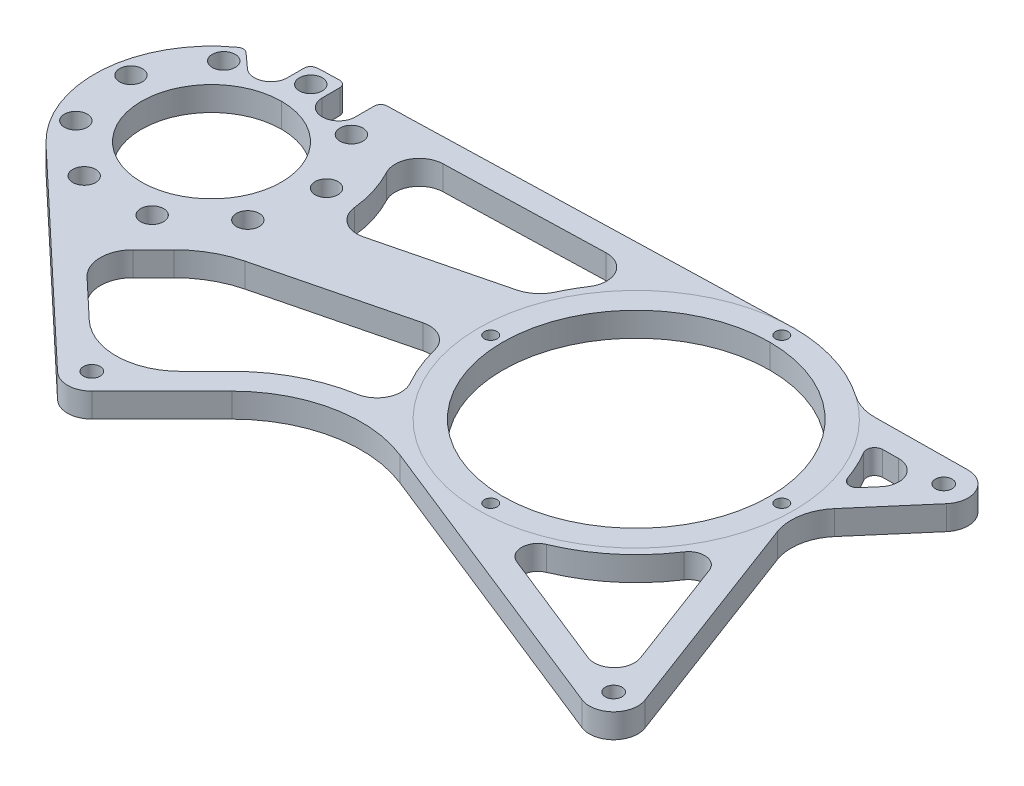
SolidWorks part; units mm, degrees
material "6061-T6 (SS)"
ref_plane "X-Y Datum" through (0, 0, 0) normal (0, 0, 1) x (1, 0, 0)
ref_plane "X-Z Datum" through (0, 0, 0) normal (0, 1, 0) x (1, 0, 0)
ref_plane "Y-Z Datum" through (0, 0, 0) normal (1, 0, 0) x (0, 0, -1)
sketch "Master Sketch " plane through (0, 0, 0) normal (0, 1, 0) x (1, 0, 0)
  line L0 (0, 0) -> (116.84, 0) construction
  line L1 (0, 0) -> (-54.61, 0) construction
  line L2 (116.84, 0) -> (228.6, 0) construction
  line L3 (228.6, 0) -> (228.6, 165.1) construction
  line L4 (123.19, 0) -> (123.19, 116.0018) construction
  line L5 (-54.61, 0) -> (-414.02, 0) construction
  line L6 (-54.61, 0) -> (-54.61, 127) construction
  line L7 (123.19, 168.4528) -> (123.19, 177.9778) construction
  line L8 (123.19, 116.0018) -> (228.6, 165.1) construction
  line L9 (123.19, 116.0018) -> (228.6, 0) construction
  line L10 (0, 0) -> (123.19, 116.0018) construction
  line L11 (0, 0) -> (-54.61, 127) construction
  line L12 (-54.61, 127) -> (123.19, 116.0018) construction
  line L13 (-54.61, 127) -> (228.6, 165.1) construction
  line L14 (0, 0) -> (0, 123.622) construction
  line L15 (-86.1521, 93.553) -> (-6.535, 18.4704)
  line L16 (-54.61, 172.974) -> (123.19, 177.9778)
  line L17 (192.5164, 124.5578) -> (212.8001, 148.1685)
  line L18 (169.599, 163.5141) -> (205.4727, 163.8999)
  line L19 (189.1339, 105.4429) -> (220.4344, 22.1488)
  line L20 (6.7352, 18.6648) -> (34.256, 46.1856)
  line L21 (207.987, 9.9519) -> (89.0101, 57.4446)
  circle A0 centre (0, 0) radius 12.7 construction
  circle A1 centre (228.6, 165.1) radius 12.7 construction
  circle A2 centre (228.6, 0) radius 12.7 construction
  circle A3 centre (-414.02, 0) radius 12.7 construction
  circle A4 centre (123.19, 116.0018) radius 52.451
  circle A5 centre (123.19, 116.0018) radius 57.15 construction
  circle A6 centre (123.19, 116.0018) radius 61.976 construction
  circle A7 centre (-54.61, 127) radius 45.974
  circle A8 centre (-54.61, 127) radius 39 construction
  circle A9 centre (205.5752, 154.3754) radius 3 construction
  circle A10 centre (211.5182, 18.7982) radius 3 construction
  circle A11 centre (0, 25.4) radius 3 construction
  circle A12 centre (0, 25.4) radius 9.525
  circle A13 centre (211.5182, 18.7982) radius 9.525
  circle A14 centre (205.5752, 154.3754) radius 9.525
  arc A17 (56.2619, 120.1418) -> (168.2859, 66.3745) centre (123.19, 116.0018) ccw construction
  arc A18 (123.19, 177.9778) -> (158.5311, 166.9138) centre (123.19, 116.0018) cw
  circle A19 centre (123.19, 116.0018) radius 67.056 construction
  arc A20 (192.5164, 124.5578) -> (189.1339, 105.4429) centre (206.9663, 112.1441) ccw
  arc A21 (169.599, 163.5141) -> (158.5311, 166.9138) centre (169.3942, 182.563) cw
  arc A22 (89.0101, 57.4446) -> (34.256, 46.1856) centre (70.177, 10.2646) ccw
  circle A23 centre (-54.61, 127) radius 25.908 construction
  circle A24 centre (-54.61, 127) radius 27.4955
  circle A25 centre (123.19, 173.1518) radius 2.5 construction
  circle A26 centre (-41.2712, 163.648) radius 6.5
  circle A27 centre (-67.9488, 163.648) radius 6.5
  point P9 (123.19, 0)
  point P23 (-54.61, 166)
  point P27 (-41.2712, 163.648)
  point P28 (-29.5413, 156.8757)
  point P29 (-20.835, 146.5)
  point P30 (-16.2025, 133.7723)
  point P31 (-16.2025, 120.2277)
  point P32 (-20.835, 107.5)
  point P33 (-29.5413, 97.1243)
  point P34 (-41.2712, 90.352)
  point P35 (-54.61, 88)
  point P36 (-67.9488, 90.352)
  point P37 (-79.6787, 97.1243)
  point P38 (-88.385, 107.5)
  point P39 (-93.0175, 120.2277)
  point P40 (-93.0175, 133.7723)
  point P41 (-88.385, 146.5)
  point P42 (-79.6787, 156.8757)
  point P43 (-67.9488, 163.648)
  point P44 (-54.61, 127)
  point P66 (190.246, 116.0018)
  point P74 (185.166, 116.0018)
  point P77 (163.0683, 163.4438)
  point P80 (74.3713, 70.0317)
  dimension "D1" = 105.41
  dimension "D2" = 25.4
  dimension "D8" = 116.0018
  dimension "D11" = 104.902
  dimension "D12" = 114.3
  dimension "D13" = 123.952
  dimension "D14" = 91.948
  dimension "D15" = 78
  dimension "D17" = 6
  dimension "D21" = 19.05
  dimension "D23" = 13
  dimension "D25" = 19.05
  dimension "D26" = 19.05
  dimension "D27" = 50.8
  dimension "D28" = 1.5875
  dimension "D30" = 51.816
  dimension "D31" = 5
  dimension "D3" = 165.1
  dimension "D4" = 171.45
  dimension "D5" = 111.76
  dimension "D6" = 116.84
  dimension "D7" = 54.61
  dimension "D9" = 642.62
  dimension "D10" = 127
  dimension "D18" = 25.4
  dimension "D19" = 25.4
  dimension "D20" = 25.4
  dimension "D22" = 228.6
  dimension "D29" = 45
  dimension "D24" = 5.08
  dimension "D16" = 18
extrude "Boss-Extrude2" add sketch "Master Sketch " along normal mid plane 9.525
hole_wizard "Ø5.0mm Dowel Hole1" positions "Sketch26" profile "Sketch27" hole size "Ø5.0" standard "ANSI Metric" end condition through all
sketch "Sketch26" plane through (0, 4.7625, 0) normal (0, 1, 0) x (1, 0, 0)
  point P5 (123.19, 173.1518)
sketch "Sketch27" plane through (123.19, 4.7625, -173.1518) normal (1, 0, 0) x (0, 0, 1)
  line L0 (0, 0) -> (0, 9.525)
  line L1 (0, 9.525) -> (2.5, 9.525)
  line L2 (2.5, 9.525) -> (2.5, 0)
  line L5 (2.5, 0) -> (0, 0)
  line L11 (0, -6.35) -> (0, 107.95) construction
  dimension "Thru Hole Dia." = 5
  dimension "Thru Hole Depth" = 9.525
pattern_circular "CirPattern4" count 4 over 360 about axis through (123.19, 0, -116.0018) along (0, 1, 0) of "Ø5.0mm Dowel Hole1"
hole_wizard "M6 Clearance Hole4" positions "Sketch20" profile "Sketch21" hole size "M6" standard "ANSI Metric" end condition through all
sketch "Sketch20" plane through (0, 4.7625, 0) normal (0, 1, 0) x (1, 0, 0)
  point P0 (205.5752, 154.3754)
  point P3 (211.5182, 18.7982)
  point P6 (0, 25.4)
  point P9 (205.5752, 154.3754)
sketch "Sketch21" plane through (205.5752, 4.7625, -154.3754) normal (1, 0, 0) x (0, 0, 1)
  line L0 (0, 0) -> (0, 9.525)
  line L1 (0, 9.525) -> (3.3, 9.525)
  line L2 (3.3, 9.525) -> (3.3, 0)
  line L5 (3.3, 0) -> (0, 0)
  line L11 (0, -6.35) -> (0, 107.95) construction
  dimension "Thru Hole Dia." = 6.6
  dimension "Thru Hole Depth" = 9.525
hole_wizard "M8 Clearance Hole1" positions "Sketch24" profile "Sketch25" hole size "M8" standard "ANSI Metric" end condition through all
sketch "Sketch24" plane through (0, 4.7625, 0) normal (0, 1, 0) x (1, 0, 0)
  point P2 (-54.61, 166)
sketch "Sketch25" plane through (-54.61, 4.7625, -166) normal (1, 0, 0) x (0, 0, 1)
  line L0 (0, 0) -> (0, 9.525)
  line L1 (0, 9.525) -> (4.5, 9.525)
  line L2 (4.5, 9.525) -> (4.5, 0)
  line L5 (4.5, 0) -> (0, 0)
  line L11 (0, -6.35) -> (0, 107.95) construction
  dimension "Thru Hole Dia." = 9
  dimension "Thru Hole Depth" = 9.525
pattern_circular "CirPattern3" count 9 over 360 about axis through (-54.61, 0, -127) along (0, 1, 0) of "M8 Clearance Hole1"
ref_plane "Plane2" through (-54.61, 0, 0) normal (1, 0, 0) x (0, 0, -1)
ref_plane "Plane1" through (123.19, 0, 0) normal (1, 0, 0) x (0, 0, -1)
split line "Split Line2"
split line "Split Line3"
ref_point "Point2"
ref_point "Point3"
sketch "Sketch28" plane through (0, 4.7625, 0) normal (0, 1, 0) x (1, 0, 0)
  circle A0 centre (123.19, 116.0018) radius 61.976 construction
  circle A1 centre (123.19, 116.0018) radius 61.976
split line "Split Line4"
sketch "Topology 3" plane through (0, 4.7625, 0) normal (0, 1, 0) x (1, 0, 0)
  line L0 (148.2326, 44.0603) -> (194.8213, 25.4632)
  line L1 (205.1941, 35.6272) -> (188.9001, 78.9873)
  line L2 (188.0448, 154.1869) -> (181.8702, 154.1205)
  line L3 (190.1271, 136.3935) -> (194.151, 141.0774)
  line L4 (185.2915, 130.7647) -> (205.5752, 154.3754) construction
  line L5 (17.4418, 42.8418) -> (27.5208, 52.9208)
  line L6 (-33.0328, 56.5514) -> (-17.9453, 42.3233)
  line L7 (119.7044, 177.8797) -> (-54.61, 172.974)
  line L8 (-86.1521, 93.553) -> (-6.535, 18.4704)
  line L9 (6.7352, 18.6648) -> (34.256, 46.1856)
  line L10 (89.0101, 57.4446) -> (207.987, 9.9519)
  line L11 (220.4344, 22.1488) -> (189.1339, 105.4429)
  line L12 (192.5164, 124.5578) -> (212.8001, 148.1685)
  line L13 (205.4727, 163.8999) -> (169.599, 163.5141)
  line L14 (119.7044, 177.8797) -> (-54.61, 172.974)
  line L15 (-86.1521, 93.553) -> (-6.535, 18.4704)
  line L16 (6.7352, 18.6648) -> (34.256, 46.1856)
  line L17 (89.0101, 57.4446) -> (207.987, 9.9519)
  line L18 (220.4344, 22.1488) -> (189.1339, 105.4429)
  line L19 (192.5164, 124.5578) -> (212.8001, 148.1685)
  line L20 (205.4727, 163.8999) -> (169.599, 163.5141)
  line L22 (-7.4578, 92.9346) -> (48.4864, 106.9206)
  line L23 (60.6168, 166.688) -> (-1.6638, 164.9353)
  line L24 (7.6514, 124.4645) -> (55.6594, 136.4665)
  line L25 (-33.2997, 74.7712) -> (-25.158, 82.9129)
  line L26 (119.9724, 168.3585) -> (-54.342, 163.4528) construction
  line L27 (-79.6171, 100.4826) -> (0, 25.4) construction
  line L28 (0, 25.4) -> (27.5208, 52.9208) construction
  line L29 (92.5413, 66.2908) -> (211.5182, 18.7982) construction
  line L30 (211.5182, 18.7982) -> (180.2176, 102.0923) construction
  line L32 (205.5752, 154.3754) -> (169.7015, 153.9896) construction
  arc A0 (123.19, 54.0258) -> (182.1581, 96.9285) centre (123.19, 116.0018) ccw
  arc A1 (148.1536, 55.8231) -> (177.6482, 80.2392) centre (123.19, 116.0018) ccw
  arc A2 (172.1385, 154.0158) -> (183.7852, 129.0114) centre (123.19, 116.0018) cw
  arc A3 (179.1759, 149.3219) -> (184.7202, 137.4188) centre (123.19, 116.0018) cw
  arc A4 (59.8962, 69.7071) -> (27.5208, 52.9208) centre (70.177, 10.2646) ccw
  arc A7 (61.4889, 110.1712) -> (82.4046, 69.3373) centre (123.19, 116.0018) ccw
  arc A8 (158.5311, 166.9138) -> (169.599, 163.5141) centre (169.3942, 182.563) ccw
  arc A9 (119.7044, 177.8797) -> (158.5311, 166.9138) centre (123.19, 116.0018) ccw
  arc A10 (-54.61, 172.974) -> (-86.1521, 93.553) centre (-54.61, 127) ccw
  arc A11 (-6.535, 18.4704) -> (6.7352, 18.6648) centre (0, 25.4) ccw
  arc A12 (89.0101, 57.4446) -> (34.256, 46.1856) centre (70.177, 10.2646) ccw
  arc A13 (207.987, 9.9519) -> (220.4344, 22.1488) centre (211.5182, 18.7982) ccw
  arc A14 (192.5164, 124.5578) -> (189.1339, 105.4429) centre (206.9663, 112.1441) ccw
  arc A15 (212.8001, 148.1685) -> (205.4727, 163.8999) centre (205.5752, 154.3754) ccw
  arc A16 (158.5311, 166.9138) -> (169.599, 163.5141) centre (169.3942, 182.563) ccw
  arc A17 (119.7044, 177.8797) -> (158.5311, 166.9138) centre (123.19, 116.0018) ccw
  arc A18 (-54.61, 172.974) -> (-86.1521, 93.553) centre (-54.61, 127) ccw
  arc A19 (-6.535, 18.4704) -> (6.7352, 18.6648) centre (0, 25.4) ccw
  arc A20 (89.0101, 57.4446) -> (34.256, 46.1856) centre (70.177, 10.2646) ccw
  arc A21 (207.987, 9.9519) -> (220.4344, 22.1488) centre (211.5182, 18.7982) ccw
  arc A22 (192.5164, 124.5578) -> (189.1339, 105.4429) centre (206.9663, 112.1441) ccw
  arc A23 (212.8001, 148.1685) -> (205.4727, 163.8999) centre (205.5752, 154.3754) ccw
  arc A24 (60.0304, 100.017) -> (66.5532, 83.8005) centre (123.19, 116.0018) ccw
  arc A25 (63.439, 132.459) -> (88.6754, 167.4777) centre (123.19, 116.0018) cw
  arc A26 (64.0981, 143.4389) -> (68.8318, 151.9162) centre (123.19, 116.0018) cw
  arc A27 (-4.1248, 132.6464) -> (-9.7981, 150.9276) centre (-54.61, 127) ccw
  arc A28 (92.5413, 66.2908) -> (27.5208, 52.9208) centre (70.177, 10.2646) ccw construction
  arc A29 (58.328, 109.8725) -> (80.3152, 66.9467) centre (123.19, 116.0018) ccw construction
  arc A30 (60.378, 133.3021) -> (86.9072, 170.1148) centre (123.19, 116.0018) cw construction
  arc A31 (123.19, 50.8508) -> (185.179, 95.9514) centre (123.19, 116.0018) ccw construction
  arc A32 (174.6461, 155.9633) -> (186.8894, 129.6779) centre (123.19, 116.0018) cw construction
  arc A33 (205.1941, 35.6272) -> (194.8213, 25.4632) centre (197.7639, 32.8351) cw
  arc A34 (188.9001, 78.9873) -> (177.6482, 80.2392) centre (182.956, 76.7536) ccw
  arc A35 (148.1536, 55.8231) -> (148.2326, 44.0603) centre (150.5867, 49.9578) ccw
  arc A36 (184.7202, 137.4188) -> (190.1271, 136.3935) centre (187.7188, 138.4625) ccw
  arc A37 (181.8702, 154.1205) -> (179.1759, 149.3219) centre (181.9043, 150.9457) ccw
  arc A38 (194.151, 141.0774) -> (188.0448, 154.1869) centre (188.1302, 146.2498) ccw
  arc A42 (48.4864, 106.9206) -> (60.0304, 100.017) centre (50.7965, 97.68) cw
  arc A43 (59.8962, 69.7071) -> (66.5532, 83.8005) centre (58.2729, 79.0927) ccw
  arc A46 (-1.6638, 164.9353) -> (-9.7981, 150.9276) centre (-1.3958, 155.4141) ccw
  arc A47 (7.6514, 124.4645) -> (-4.1248, 132.6464) centre (5.3412, 133.7051) cw
  arc A48 (55.6594, 136.4665) -> (64.0981, 143.4389) centre (52.5792, 148.7873) ccw
  arc A49 (68.8318, 151.9162) -> (60.6168, 166.688) centre (60.8847, 157.1668) ccw
  arc A50 (-33.2997, 74.7712) -> (-33.0328, 56.5514) centre (-24.3195, 65.7909) ccw
  arc A51 (-6.535, 18.4704) -> (6.7352, 18.6648) centre (0, 25.4) ccw
  arc A55 (-7.4578, 92.9346) -> (-25.158, 82.9129) centre (1.7828, 55.9721) ccw
  arc A59 (17.4418, 42.8418) -> (-17.9453, 42.3233) centre (-0.5187, 60.8023) cw
  point P97 (6.7352, 32.1352)
  dimension "D11" = 7.9375
  dimension "D12" = 6.35
  dimension "D13" = 12.7
  dimension "D14" = 7.9375
  dimension "D15" = 25.4
  dimension "D16" = 38.1
  dimension "D17" = 9.525
  dimension "D21" = 9.525
  dimension "D22" = 9.525
  dimension "D23" = 12.7
  dimension "D24" = 9.525
  dimension "D25" = 50.8
  dimension "D20" = 26.924
  dimension "D26" = 52
  dimension "D1" = 0
  dimension "D2" = 9.525
  dimension "D3" = 3.175
  dimension "D4" = 9.525
  dimension "D5" = 3.175
  dimension "D6" = 9.525
  dimension "D7" = 9.525
  dimension "D8" = 3.175
  dimension "D9" = 9.525
  dimension "D10" = 3.175
extrude "Cut-Extrude2" cut sketch "Topology 3" against normal through all contours A1 A35 L0 A33 L1 A34 | L3 A38 L2 A37 A3 A36 | A26 A49 L23 A46 A27 A47 L24 A48 | A59 L5 A4 A43 A24 A42 L22 A55 L25 A50 L6
sketch "Sketch29" plane through (0, -4.7625, 0) normal (0, -1, 0) x (1, 0, 0)
  line L0 (-72.3056, -158.8243) -> (-79.7134, -165.5153)
  line L1 (-61.4488, -163.648) -> (-61.4488, -172.4625)
  line L2 (-47.7712, -163.648) -> (-47.7712, -173.1665)
  line L3 (-34.7712, -163.648) -> (-34.7712, -173.5323)
  line L4 (-54.61, -172.974) -> (123.19, -177.9778) construction
  line L5 (-47.7712, -173.1665) -> (-34.7712, -173.5323)
  circle A1 centre (-41.2712, -163.648) radius 6.5 construction
  circle A2 centre (-67.9488, -163.648) radius 6.5 construction
  circle A3 centre (-41.2712, -163.648) radius 6.5 construction
  circle A4 centre (-67.9488, -163.648) radius 6.5 construction
  arc A5 (-86.1521, -93.553) -> (-54.61, -172.974) centre (-54.61, -127) ccw construction
  arc A6 (-86.1521, -93.553) -> (-54.61, -172.974) centre (-54.61, -127) ccw construction
  arc A7 (-72.3056, -158.8243) -> (-61.4488, -163.648) centre (-67.9488, -163.648) ccw
  arc A8 (-61.4488, -172.4625) -> (-79.7134, -165.5153) centre (-54.61, -127) cw
  arc A9 (-47.7712, -163.648) -> (-34.7712, -163.648) centre (-41.2712, -163.648) ccw
  dimension "D1" = 7.4078
extrude "Cut-Extrude3" cut sketch "Sketch29" against normal through all
fillet "Fillet1" radius 2.54 4 edges at (-79.7134, 0, -165.5153) (-61.4488, 0, -172.4625) (-47.7712, 0, -173.1665) (-34.7712, 0, -173.5323)
